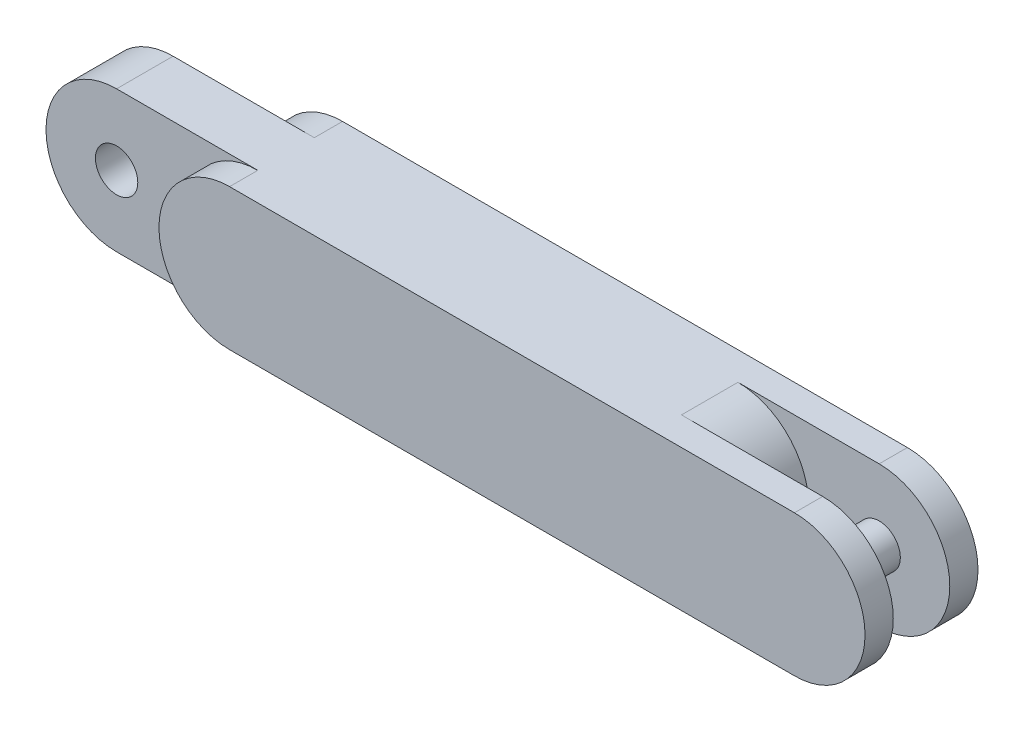
SolidWorks part; units mm, degrees
material "1060 Alloy"
ref_plane "Front Plane" through (0, 0, 0) normal (0, 0, 1) x (1, 0, 0)
ref_plane "Top Plane" through (0, 0, 0) normal (0, 1, 0) x (1, 0, 0)
ref_plane "Right Plane" through (0, 0, 0) normal (1, 0, 0) x (0, 0, -1)
sketch "Sketch4" plane through (0, 0, 0) normal (0, 0, 1) x (1, 0, 0)
  line L0 (-250, 0) -> (250, 0) construction
  line L1 (-250, 50) -> (250, 50)
  line L2 (-250, -50) -> (250, -50)
  arc A0 (-250, 50) -> (-250, -50) centre (-250, 0) ccw
  arc A1 (250, -50) -> (250, 50) centre (250, 0) ccw
  point P3 (0, 0)
  point P8 (110.1525, 0)
  point P9 (-250, 0)
  point P10 (0, 0)
  dimension "D2" = 50
  dimension "D1" = 500
extrude "Boss-Extrude2" add sketch "Sketch4" along normal mid plane 80
sketch "Sketch5" plane through (0, 0, 40) normal (0, 0, 1) x (1, 0, 0)
  line L0 (-150, 50) -> (-250, 50)
  line L1 (-250, -50) -> (-150, -50)
  arc A0 (-250, 50) -> (-250, -50) centre (-250, 0) ccw
  arc A2 (-150, 50) -> (-150, -50) centre (-150, 0) ccw
extrude "Cut-Extrude2" cut sketch "Sketch5" against normal blind 20
sketch "Sketch6" plane through (0, 0, -40) normal (0, 0, -1) x (-1, 0, 0)
  line L0 (150, 50) -> (250, 50)
  line L1 (150, -50) -> (250, -50)
  arc A0 (250, -50) -> (250, 50) centre (250, 0) ccw
  arc A2 (150, -50) -> (150, 50) centre (150, 0) ccw
extrude "Cut-Extrude3" cut sketch "Sketch6" against normal blind 20
sketch "Sketch9" plane through (0, 0, 20) normal (0, 0, 1) x (1, 0, 0)
  circle A0 centre (-250, 0) radius 15
extrude "Cut-Extrude5" cut sketch "Sketch9" against normal blind 40
ref_plane "Plane1" through (0, 0, 0) normal (0, 0, 1) x (1, 0, 0)
sketch "Sketch10" plane through (0, 0, 0) normal (0, 0, 1) x (1, 0, 0)
  line L0 (150, 50) -> (250, 50)
  line L1 (150, -50) -> (250, -50)
  arc A2 (150, -50) -> (150, 50) centre (150, 0) ccw
  arc A3 (250, -50) -> (250, 50) centre (250, 0) ccw
extrude "Cut-Extrude6" cut sketch "Sketch10" against normal mid plane 40
sketch "Sketch11" plane through (0, 0, 40) normal (0, 0, 1) x (1, 0, 0)
  circle A0 centre (250, 0) radius 15
extrude "Boss-Extrude3" add sketch "Sketch11" against normal blind 80
sketch "Sketch12" plane through (0, 0, 0) normal (0, 0, 1) x (1, 0, 0)
  point P0 (-250, 0)
  point P1 (0, 0)
  point P3 (0, 0)
